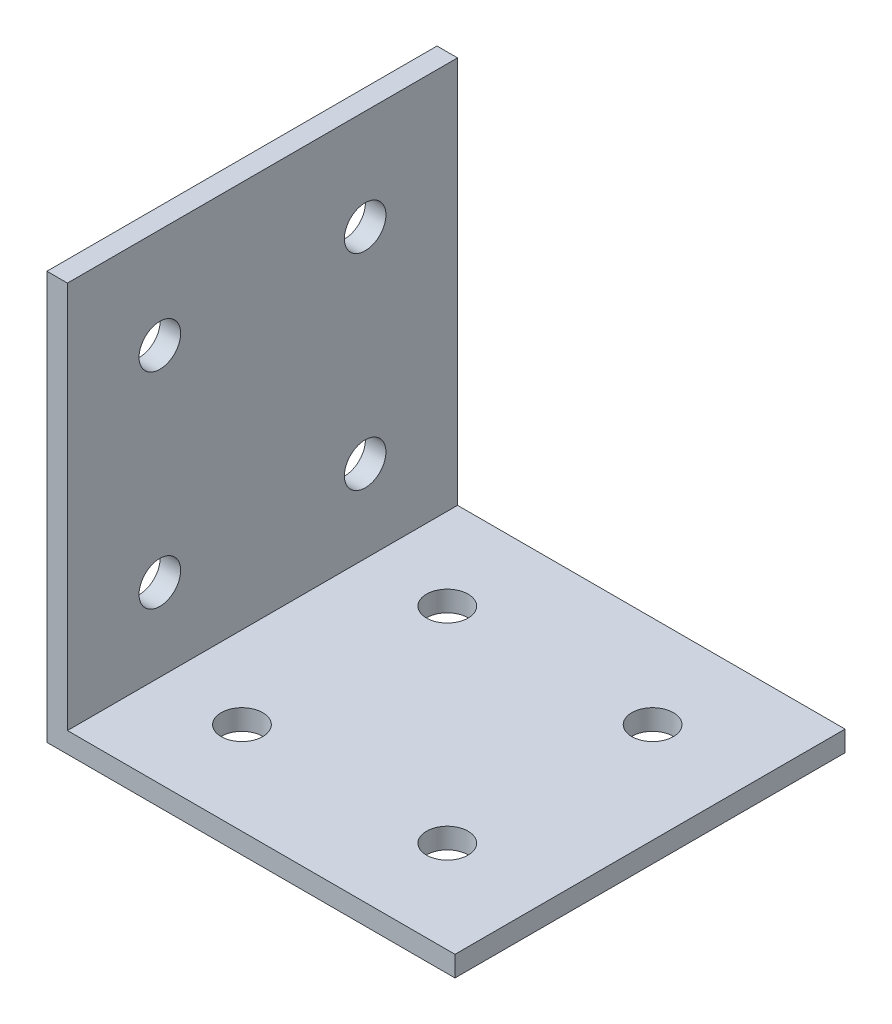
SolidWorks part; units mm, degrees
ref_plane "Front Plane" through (0, 0, 0) normal (0, 0, 1) x (1, 0, 0)
ref_plane "Top Plane" through (0, 0, 0) normal (0, 1, 0) x (1, 0, 0)
ref_plane "Right Plane" through (0, 0, 0) normal (1, 0, 0) x (0, 0, -1)
sketch "Sketch1" plane through (0, 0, 0) normal (0, 1, 0) x (1, 0, 0)
  line L0 (0, 0) -> (20, 0) construction
  line L1 (20, -20) -> (60, -20) construction
  line L2 (20, -20) -> (20, 20) construction
  line L3 (20, 20) -> (60, 20) construction
  line L4 (60, -20) -> (60, 20) construction
  line L5 (20, -20) -> (60, 20) construction
  line L6 (20, 20) -> (60, -20) construction
  line L8 (0, 38) -> (79.5, 38)
  line L9 (0, 38) -> (0, -38)
  line L10 (0, -38) -> (79.5, -38)
  line L11 (79.5, 38) -> (79.5, -38)
  circle A0 centre (20, 20) radius 4.05
  circle A1 centre (60, 20) radius 4.05
  circle A2 centre (60, -20) radius 4.05
  circle A3 centre (20, -20) radius 4.05
  point P0 (40, 0)
  dimension "D3" = 8.1
  dimension "D1" = 40
  dimension "D2" = 20
  dimension "D4" = 76
  dimension "D5" = 79.5
extrude "Boss-Extrude1" add sketch "Sketch1" along normal blind 79.5
sketch "Sketch2" plane through (0, 0, 0) normal (1, 0, 0) x (0, 0, -1)
  line L0 (0, 20) -> (0, 0) construction
  line L1 (-20, 60) -> (20, 60) construction
  line L2 (-20, 60) -> (-20, 20) construction
  line L3 (-20, 20) -> (20, 20) construction
  line L4 (20, 60) -> (20, 20) construction
  line L5 (-20, 60) -> (20, 20) construction
  line L6 (-20, 20) -> (20, 60) construction
  circle A0 centre (-20, 60) radius 4.05
  circle A1 centre (20, 60) radius 4.05
  circle A2 centre (20, 20) radius 4.05
  circle A3 centre (-20, 20) radius 4.05
  point P0 (0, 40)
  dimension "D3" = 8.1
  dimension "D1" = 40
  dimension "D2" = 20
extrude "Cut-Extrude1" cut sketch "Sketch2" along normal blind 79.5
sketch "Sketch3" plane through (0, 0, 0) normal (0, 0, 1) x (1, 0, 0)
  line L0 (4, 73.8431) -> (4, 4)
  line L1 (4, 4) -> (73.8431, 4)
  line L2 (73.8431, 4) -> (4, 73.8431)
  line L3 (4, 79.5) -> (79.5, 4)
  line L4 (79.5, 4) -> (79.5, 79.5)
  line L5 (79.5, 79.5) -> (4, 79.5)
  line L6 (0, 79.5) -> (0, 0) construction
  line L7 (0, 0) -> (79.5, 0) construction
  line L8 (0, 79.5) -> (79.5, 79.5) construction
  line L9 (79.5, 79.5) -> (79.5, 0) construction
  point P11 (70.6002, 4)
  point P12 (2.9651, 79.5)
  point P15 (79.5, 0.7626)
  point P18 (79.5, 79.5)
  point P19 (79.5, 4)
  dimension "D1" = 4
  dimension "D2" = 4
  dimension "D3" = 4
extrude "Cut-Extrude2" cut sketch "Sketch3" against normal blind 79.5 and the other way blind 79.5
sketch "Sketch4" plane through (0, 0, 0) normal (0, 0, 1) x (1, 0, 0)
  line L1 (4, 4) -> (84.7718, 4)
  line L2 (4, 4) -> (4, 80.5254)
  line L3 (4, 80.5254) -> (84.7718, 80.5254)
  line L4 (84.7718, 4) -> (84.7718, 80.5254)
extrude "Cut-Extrude3" cut sketch "Sketch4" against normal blind 79.5 and the other way blind 79.5
